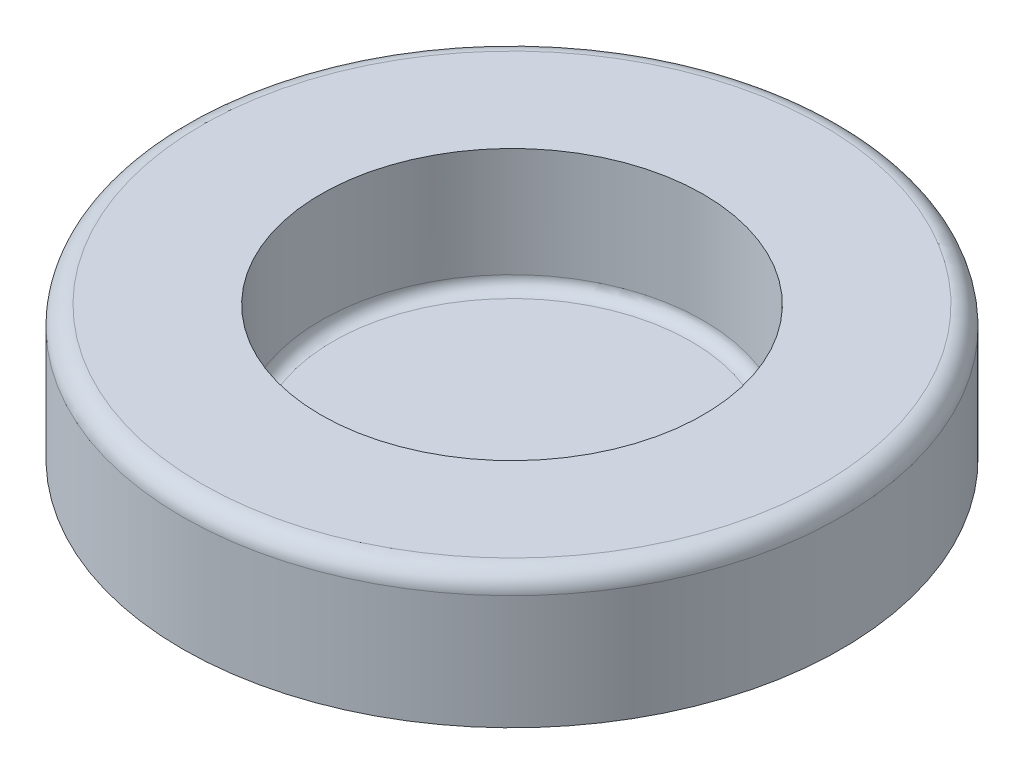
SolidWorks part; units mm, degrees
ref_plane "Front Plane" through (0, 0, 0) normal (0, 0, 1) x (1, 0, 0)
ref_plane "Top Plane" through (0, 0, 0) normal (0, 1, 0) x (1, 0, 0)
ref_plane "Right Plane" through (0, 0, 0) normal (1, 0, 0) x (0, 0, -1)
sketch "Sketch1" plane through (0, 0, 0) normal (0, 1, 0) x (1, 0, 0)
  circle A0 centre (0, 0) radius 4.0005
  circle A1 centre (0, 0) radius 6.8961
  dimension "D1" = 8.001
  dimension "D2" = 13.7922
extrude "Boss-Extrude1" add sketch "Sketch1" along normal blind 2.794
sketch "Sketch2" plane through (0, 0, 0) normal (0, -1, 0) x (1, 0, 0)
  circle A0 centre (0, 0) radius 4.0005 construction
  circle A1 centre (0, 0) radius 4.0005
extrude "Boss-Extrude2" add sketch "Sketch2" against normal blind 0.254
sketch "Sketch4" plane through (0, 0, 0) normal (0, -1, 0) x (1, 0, 0)
  circle A1 centre (0, 0) radius 6.8961
  circle A2 centre (0, 0) radius 6.8961
  dimension "D1" = 0
fillet "Fillet1" radius 0.254 1 edges at (0, 0.254, -4.0005)
fillet "Fillet3" radius 0.4 1 edges at (0, 2.794, 6.8961)
